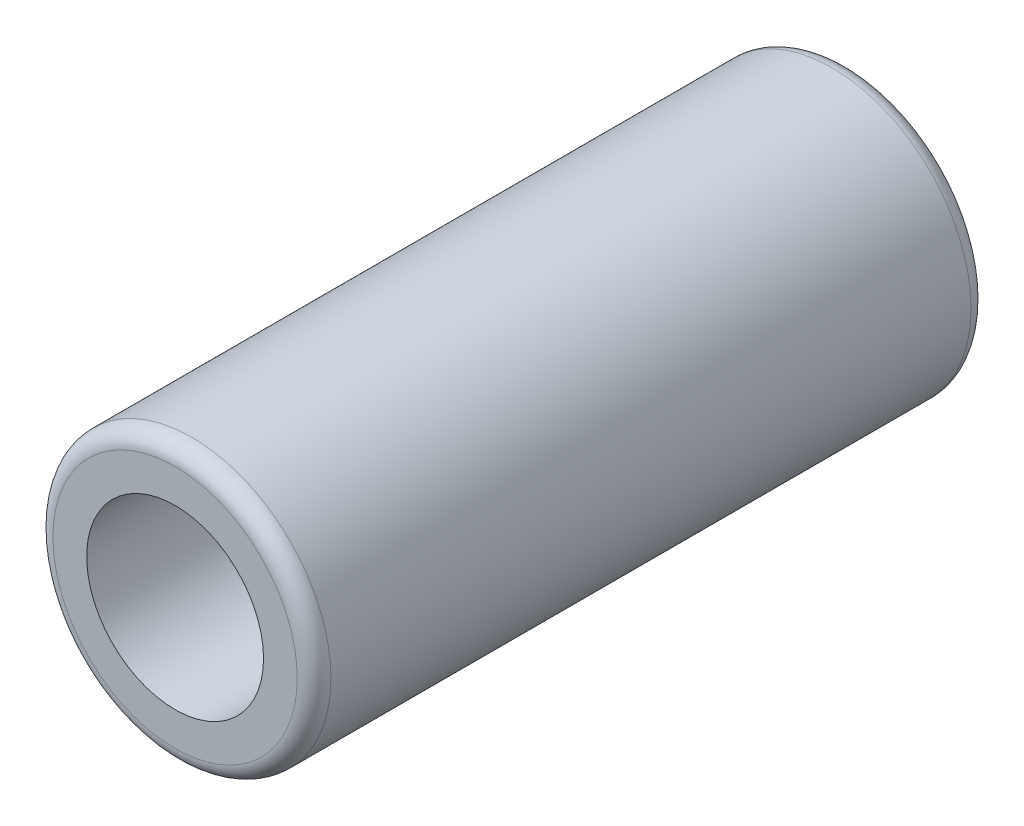
SolidWorks part; units mm, degrees
ref_plane "Přední rovina" through (0, 0, 0) normal (0, 0, 1) x (1, 0, 0)
ref_plane "Horní rovina" through (0, 0, 0) normal (0, 1, 0) x (1, 0, 0)
ref_plane "Pravá rovina" through (0, 0, 0) normal (1, 0, 0) x (0, 0, -1)
sketch "Skica1" plane through (0, 0, 0) normal (0, 0, 1) x (1, 0, 0)
  circle A0 centre (0, 0) radius 5.25
  circle A1 centre (0, 0) radius 8.25
  dimension "D1" = 10.5
  dimension "D2" = 3
extrude "Přidat vysunutím1" add sketch "Skica1" along normal blind 40
fillet "Zaoblit1" radius 1 2 edges at (8.25, 0, 0) (8.25, 0, 40)
